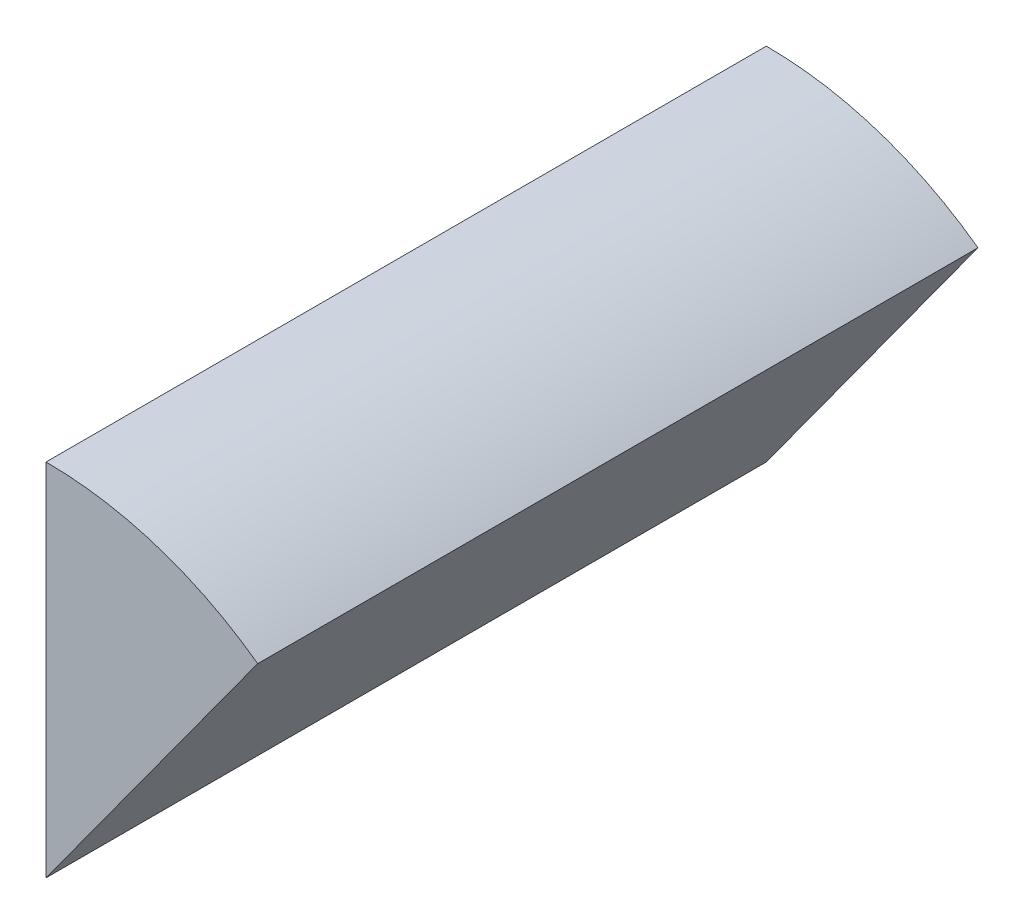
SolidWorks part; units mm, degrees
ref_plane "Alzado" through (0, 0, 0) normal (0, 0, 1) x (1, 0, 0)
ref_plane "Planta" through (0, 0, 0) normal (0, 1, 0) x (1, 0, 0)
ref_plane "Vista lateral" through (0, 0, 0) normal (1, 0, 0) x (0, 0, -1)
sketch "Croquis1" plane through (0, 0, 0) normal (0, 0, 1) x (1, 0, 0)
  line L0 (0, 25) -> (0, 0)
  line L1 (0, 0) -> (14.6946, 20.2254)
  arc A0 (14.6946, 20.2254) -> (0, 25) centre (0, 0) ccw
  dimension "D1" = 50
  dimension "D2" = 36
extrude "Saliente-Extruir1" add sketch "Croquis1" along normal blind 50
sketch "Croquis2" plane through (0, 0, 0) normal (0, 0, -1) x (-1, 0, 0)
  circle A0 centre (-5.7496, 18.3392) radius 4.9637
extrude "Cortar-Extruir1" cut sketch "Croquis2" against normal blind 10
